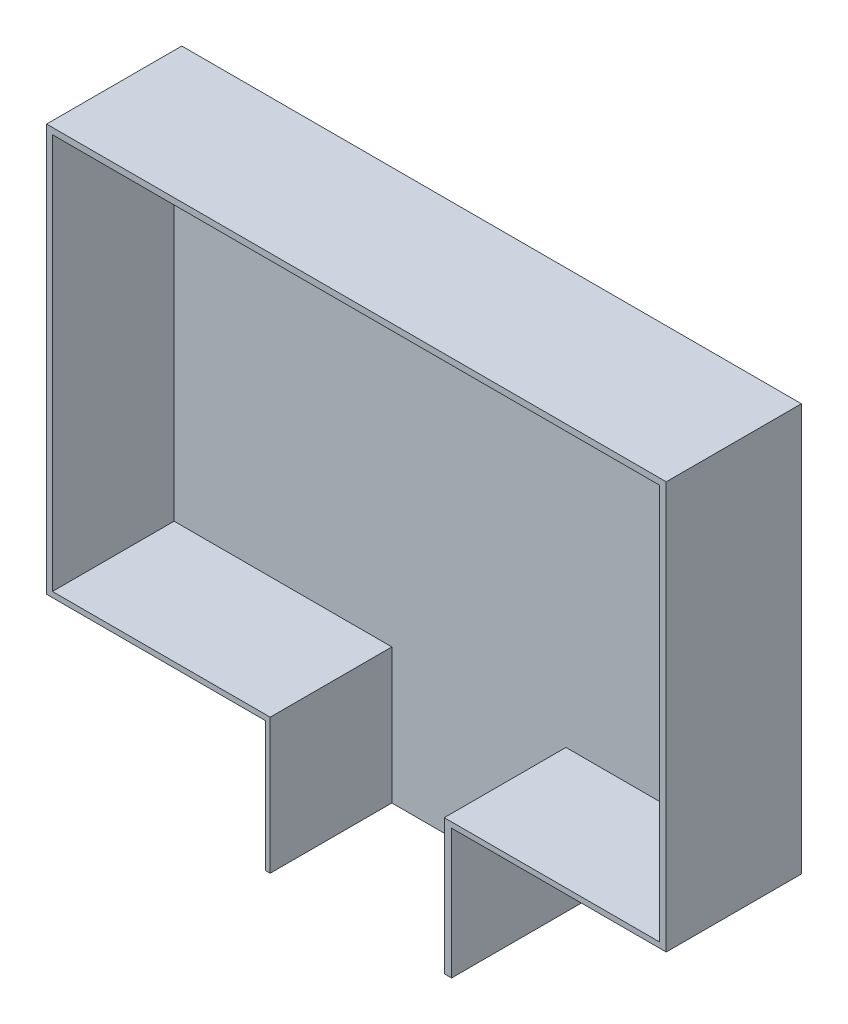
SolidWorks part; units mm, degrees
ref_plane "Front Plane" through (0, 0, 0) normal (0, 0, 1) x (1, 0, 0)
ref_plane "Top Plane" through (0, 0, 0) normal (0, 1, 0) x (1, 0, 0)
ref_plane "Right Plane" through (0, 0, 0) normal (1, 0, 0) x (0, 0, -1)
sketch "Sketch1" plane through (0, 0, 0) normal (0, 0, 1) x (1, 0, 0)
  line L1 (141.1472, 21.5707) -> (186.9809, 21.5707)
  line L2 (141.1472, 21.5707) -> (141.1472, -8.5544)
  line L3 (141.1472, -8.5544) -> (186.9809, -8.5544)
  line L4 (186.9809, 21.5707) -> (186.9809, -8.5544)
  line L5 (157.342, -18.1544) -> (171.1053, -18.1544)
  line L6 (157.342, -18.1544) -> (157.342, -8.5544)
  line L7 (157.342, -8.5544) -> (171.1053, -8.5544)
  line L8 (171.1053, -18.1544) -> (171.1053, -8.5544)
  dimension "D1" = 45.8338
  dimension "D2" = 30.1251
  dimension "D3" = 13.7633
  dimension "D4" = 9.6
extrude "Boss-Extrude1" add sketch "Sketch1" along normal blind 10
sketch "Sketch2" plane through (0, 0, 10) normal (0, 0, 1) x (1, 0, 0)
  line L0 (141.5802, 21.1058) -> (186.477, 21.1058)
  line L1 (141.5802, 21.1058) -> (141.5802, -8.1544)
  line L2 (141.5802, -8.1544) -> (186.477, -8.1544)
  line L3 (186.477, 21.1058) -> (186.477, -8.1544)
  line L4 (157.342, -18.1544) -> (171.1053, -18.1544) construction
  line L5 (157.6859, -8.1544) -> (170.5629, -8.1544)
  line L6 (157.6859, -8.1544) -> (157.6859, -18.1544)
  line L7 (157.6859, -18.1544) -> (170.5629, -18.1544)
  line L8 (170.5629, -8.1544) -> (170.5629, -18.1544)
  line M14 (157.342, -18.1544) -> (171.1053, -18.1544)
  dimension "D1" = 10
extrude "Cut-Extrude1" cut sketch "Sketch2" against normal blind 9 contours L3 L0 L1 L2 | L8 L2 L6 M14
